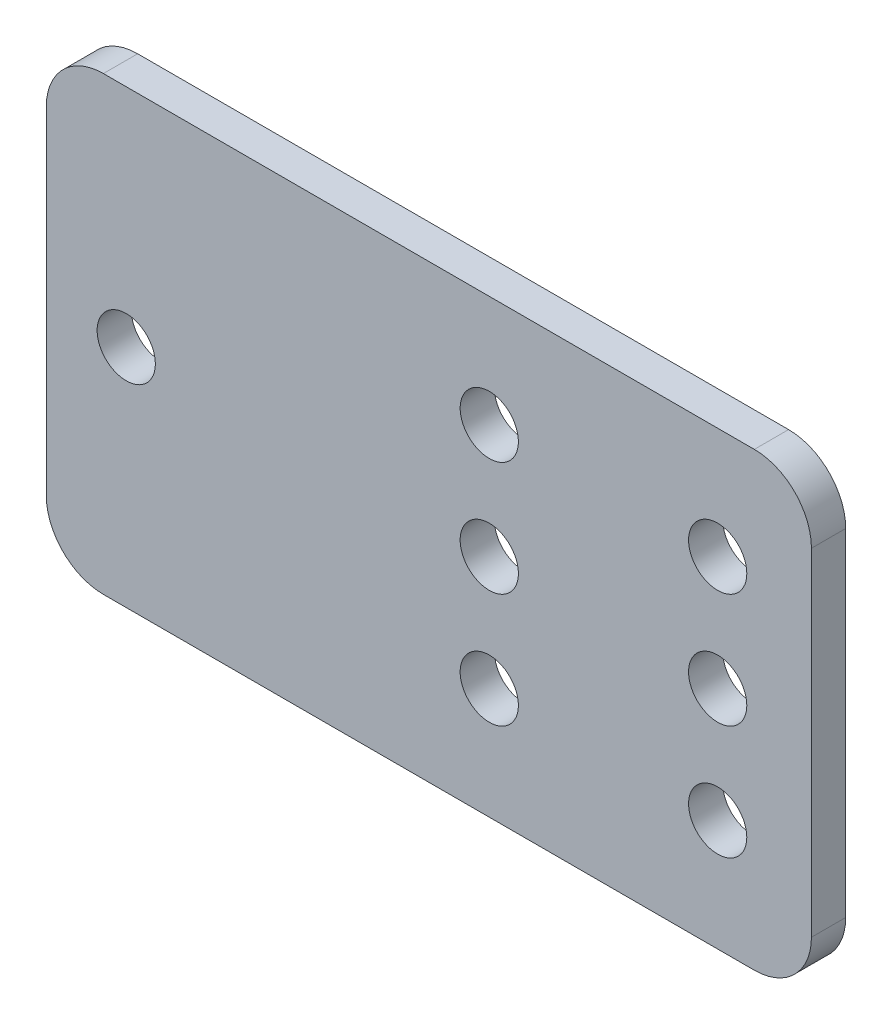
SolidWorks part; units mm, degrees
ref_plane "Plan de face" through (0, 0, 0) normal (0, 0, 1) x (1, 0, 0)
ref_plane "Plan de dessus" through (0, 0, 0) normal (0, 1, 0) x (1, 0, 0)
ref_plane "Plan de droite" through (0, 0, 0) normal (1, 0, 0) x (0, 0, -1)
sketch "Esquisse1" plane through (0, 0, 0) normal (0, 0, 1) x (1, 0, 0)
  line L0 (0, 0) -> (5.29, 0) construction
  line L1 (-28.5, -19.75) -> (28.5, -19.75)
  line L2 (-33.5, -14.75) -> (-33.5, 14.75)
  line L3 (-28.5, 19.75) -> (28.5, 19.75)
  line L4 (33.5, -14.75) -> (33.5, 14.75)
  line L5 (-33.5, -19.75) -> (33.5, 19.75) construction
  line L6 (-33.5, 19.75) -> (33.5, -19.75) construction
  line L7 (5.29, 0) -> (5.29, 10) construction
  circle A0 centre (5.29, 10) radius 2.55
  circle A1 centre (25.29, 10) radius 2.55
  circle A2 centre (5.29, 0) radius 2.55
  circle A3 centre (25.29, 0) radius 2.55
  circle A4 centre (5.29, -10) radius 2.55
  circle A5 centre (25.29, -10) radius 2.55
  circle A6 centre (-26.5, 0) radius 2.55
  arc A7 (-28.5, -19.75) -> (-33.5, -14.75) centre (-28.5, -14.75) cw
  arc A8 (28.5, -19.75) -> (33.5, -14.75) centre (28.5, -14.75) ccw
  arc A9 (28.5, 19.75) -> (33.5, 14.75) centre (28.5, 14.75) cw
  arc A10 (-33.5, 14.75) -> (-28.5, 19.75) centre (-28.5, 14.75) cw
  point P0 (0, 0)
  dimension "D5" = 5.1
  dimension "D9" = 5.1
  dimension "D11" = 5
  dimension "D1" = 67
  dimension "D2" = 39.5
  dimension "D3" = 10
  dimension "D4" = 38.79
  dimension "D8" = 20
  dimension "D10" = 7
  dimension "D6" = 2
  dimension "D7" = 3
extrude "Boss.-Extru.1" add sketch "Esquisse1" along normal mid plane 3
